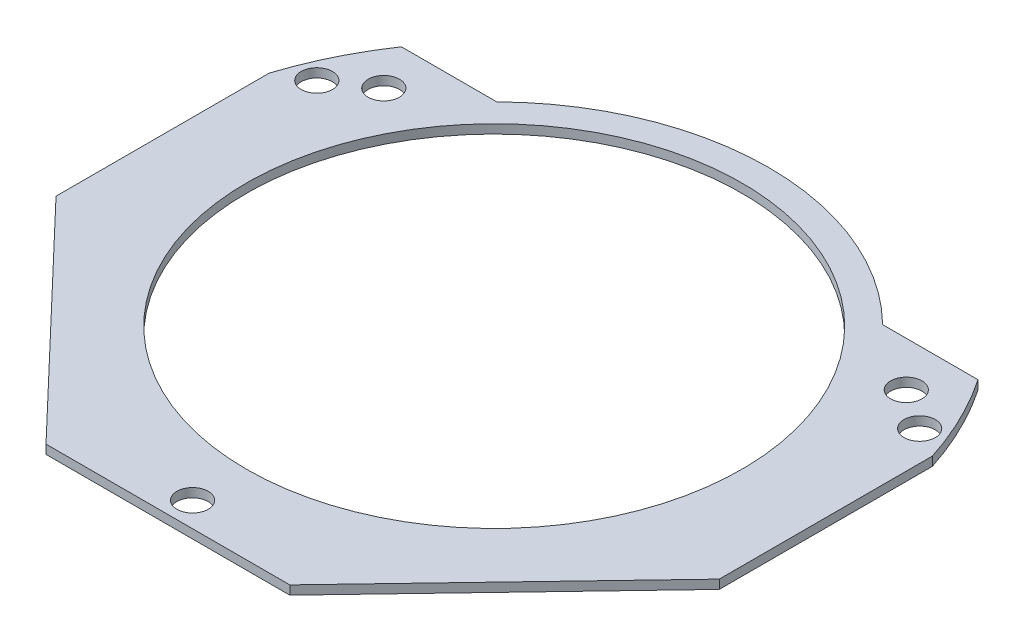
SolidWorks part; units mm, degrees
ref_plane "정면" through (0, 0, 0) normal (0, 0, 1) x (1, 0, 0)
ref_plane "윗면" through (0, 0, 0) normal (0, 1, 0) x (1, 0, 0)
ref_plane "우측면" through (0, 0, 0) normal (1, 0, 0) x (0, 0, -1)
sketch "스케치1" plane through (0, 0, 0) normal (0, 1, 0) x (1, 0, 0)
  circle A0 centre (0, 0) radius 39
  dimension "D1" = 78
extrude "보스-돌출1" add sketch "스케치1" along normal blind 1
sketch "스케치2" plane through (0, 1, 0) normal (0, 1, 0) x (1, 0, 0)
  line L0 (29.25, 16.8875) -> (0, 0) construction
  line L1 (0, 0) -> (-29.25, 16.8875) construction
  line L2 (0, 0) -> (0, -33.775) construction
  circle A0 centre (29.25, 16.8875) radius 1.75
  circle A1 centre (-29.25, 16.8875) radius 1.75
  circle A2 centre (0, -33.775) radius 1.75
  dimension "D4" = 3.5
  dimension "D1" = 120
  dimension "D2" = 120
  dimension "D3" = 58.5
extrude "컷-돌출1" cut sketch "스케치2" against normal blind 1
sketch "스케치3" plane through (0, 1, 0) normal (0, 1, 0) x (1, 0, 0)
  circle A0 centre (0, 0) radius 27.75
  dimension "D1" = 55.5
extrude "컷-돌출2" cut sketch "스케치3" against normal blind 1
sketch "스케치4" plane through (0, 1, 0) normal (0, 1, 0) x (1, 0, 0)
  line L0 (0, 0) -> (0, 27.75) construction
  line L1 (29.25, 16.8875) -> (29.25, 13.8875) construction
  line L2 (29.25, 13.8875) -> (33.75, 13.8875) construction
  circle A0 centre (33.75, 13.8875) radius 1.75
  circle A1 centre (0, 0) radius 27.75 construction
  circle A2 centre (-33.75, 13.8875) radius 1.75
  dimension "D3" = 3.5
  dimension "D1" = 3
  dimension "D2" = 4.5
extrude "컷-돌출3" cut sketch "스케치4" against normal blind 1
sketch "스케치5" plane through (0, 1, 0) normal (0, 1, 0) x (1, 0, 0)
  line L0 (-41.1653, 21.8875) -> (-21.5986, 21.8875)
  line L1 (39.254, 21.8875) -> (39.254, 46.5153)
  line L2 (39.254, 46.5153) -> (-41.1653, 46.5153)
  line L3 (-41.1653, 46.5153) -> (-41.1653, 21.8875)
  line L4 (21.5986, 21.8875) -> (39.254, 21.8875)
  arc A0 (21.5986, 21.8875) -> (-21.5986, 21.8875) centre (0, 0) ccw
  circle A1 centre (0, 0) radius 27.75 construction
  circle A2 centre (29.25, 16.8875) radius 1.75 construction
  dimension "D1" = 3
  dimension "D2" = 5
extrude "컷-돌출4" cut sketch "스케치5" against normal blind 1
sketch "스케치6" plane through (0, 1, 0) normal (0, 1, 0) x (1, 0, 0)
  line L0 (0, 0) -> (0, -39) construction
  line L1 (37.1302, 19.9611) -> (37.1302, -11.9309)
  line L2 (37.1302, -11.9309) -> (13.6507, -36.533)
  line L3 (13.6507, -36.533) -> (-13.6507, -36.533)
  line L4 (-13.6507, -36.533) -> (-37.1302, -11.9309)
  line L5 (-37.1302, -11.9309) -> (-37.1302, 19.9611)
  line L6 (-37.1302, 19.9611) -> (-57.2086, 19.9611)
  line L7 (-57.2086, 19.9611) -> (-57.2086, -51.2433)
  line L8 (-57.2086, -51.2433) -> (54.0976, -51.2433)
  line L9 (54.0976, -51.2433) -> (54.0976, 19.9611)
  line L10 (54.0976, 19.9611) -> (37.1302, 19.9611)
  line L11 (37.1302, -11.9309) -> (-37.1302, -11.9309) construction
  line L12 (-37.1302, 19.9611) -> (37.1302, 19.9611) construction
  line L13 (37.1302, 19.9611) -> (36.8886, 19.6454) construction
  arc A0 (-32.2791, 21.8875) -> (32.2791, 21.8875) centre (0, 0) ccw construction
extrude "컷-돌출5" cut sketch "스케치6" against normal blind 1
